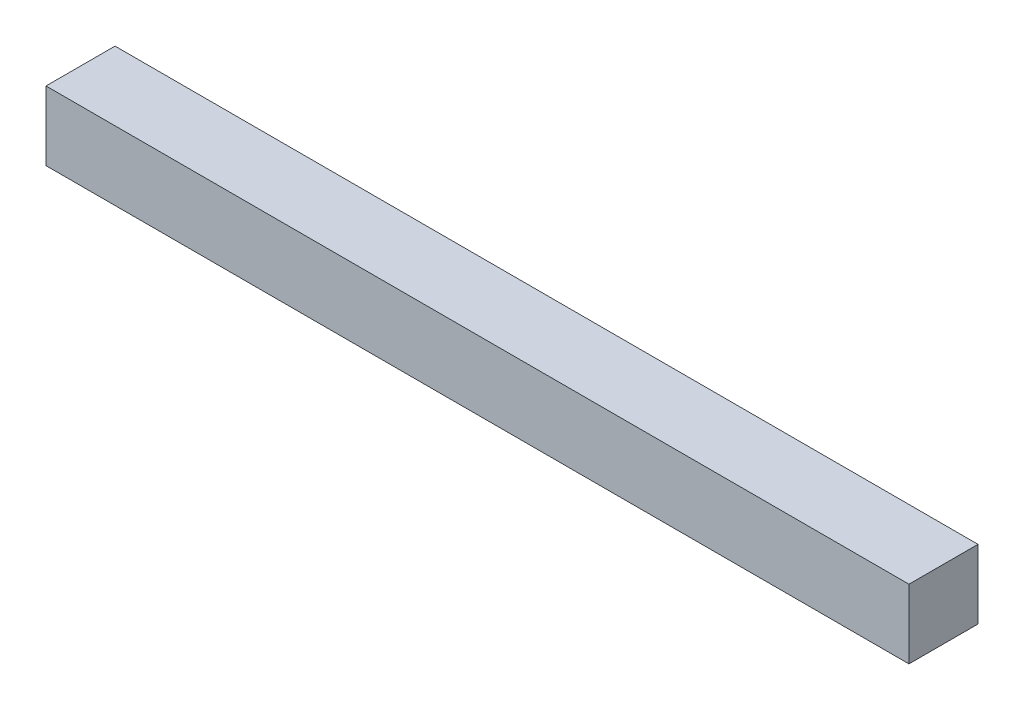
SolidWorks part; units mm, degrees
ref_plane "Front Plane" through (0, 0, 0) normal (0, 0, 1) x (1, 0, 0)
ref_plane "Top Plane" through (0, 0, 0) normal (0, 1, 0) x (1, 0, 0)
ref_plane "Right Plane" through (0, 0, 0) normal (1, 0, 0) x (0, 0, -1)
sketch "Sketch1" plane through (0, 0, 0) normal (0, 0, 1) x (1, 0, 0)
  line L1 (0, 0) -> (200, 0)
  line L2 (0, 0) -> (0, 16)
  line L3 (0, 16) -> (200, 16)
  line L4 (200, 0) -> (200, 16)
  dimension "D1" = 16
  dimension "D2" = 200
extrude "Boss-Extrude1" add sketch "Sketch1" along normal blind 16
